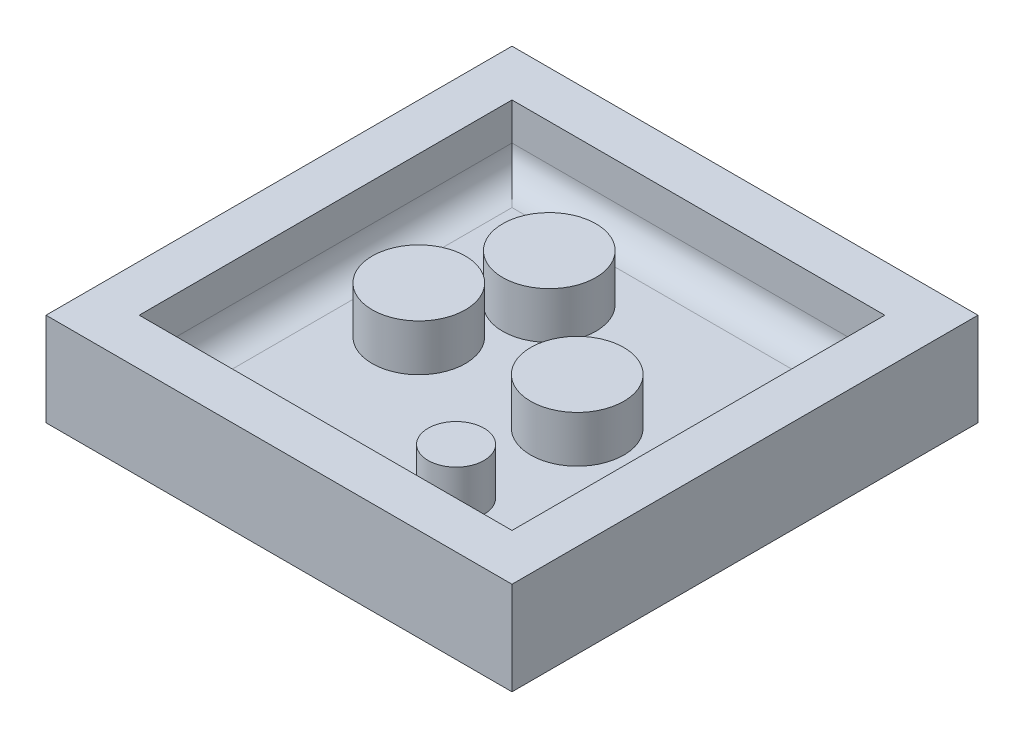
SolidWorks part; units mm, degrees
ref_plane "Front Plane" through (0, 0, 0) normal (0, 0, 1) x (1, 0, 0)
ref_plane "Top Plane" through (0, 0, 0) normal (0, 1, 0) x (1, 0, 0)
ref_plane "Right Plane" through (0, 0, 0) normal (1, 0, 0) x (0, 0, -1)
sketch "Sketch1" plane through (0, 0, 0) normal (0, 1, 0) x (1, 0, 0)
  line L1 (0, 0) -> (50, 0)
  line L2 (0, 0) -> (0, 50)
  line L3 (0, 50) -> (50, 50)
  line L4 (50, 0) -> (50, 50)
  dimension "D1" = 50
  dimension "D2" = 50
extrude "Boss-Extrude1" add sketch "Sketch1" along normal blind 10
sketch "Sketch2" plane through (0, 10, 0) normal (0, 1, 0) x (1, 0, 0)
  line L0 (0, 25) -> (50, 25) construction
  line L1 (5, 45) -> (45, 45)
  line L2 (5, 45) -> (5, 5)
  line L3 (5, 5) -> (45, 5)
  line L4 (45, 45) -> (45, 5)
  line L5 (0, 50) -> (0, 0) construction
  line L6 (50, 0) -> (50, 50) construction
  dimension "D1" = 20
  dimension "D2" = 5
  dimension "D3" = 5
  dimension "D4" = 20
extrude "Cut-Extrude1" cut sketch "Sketch2" against normal blind 7
fillet "Fillet1" radius 3 4 edges at (45, 3, -25) (25, 3, -5) (5, 3, -25) (25, 3, -45)
sketch "Sketch3" plane through (0, 3, 0) normal (0, 1, 0) x (1, 0, 0)
  line L0 (25, 45) -> (25, 5) construction
  line L1 (45, 45) -> (5, 45) construction
  line L2 (5, 5) -> (45, 5) construction
  line L3 (5, 25) -> (45, 25) construction
  line L4 (5, 5) -> (5, 45) construction
  line L5 (45, 45) -> (45, 5) construction
  line L6 (5, 45) -> (45, 45) construction
  circle A0 centre (19, 35) radius 5
  circle A1 centre (32, 25) radius 5
  circle A2 centre (15, 25) radius 5
  circle A3 centre (32, 12) radius 3
  point P22 (0, 0)
  point P23 (0, 0)
  dimension "D1" = 10
  dimension "D8" = 6
  dimension "D2" = 10
  dimension "D3" = 10
  dimension "D4" = 10
  dimension "D5" = 7
  dimension "D6" = 13
  dimension "D7" = 7
  dimension "D9" = 6
extrude "Boss-Extrude2" add sketch "Sketch3" along normal blind 5
